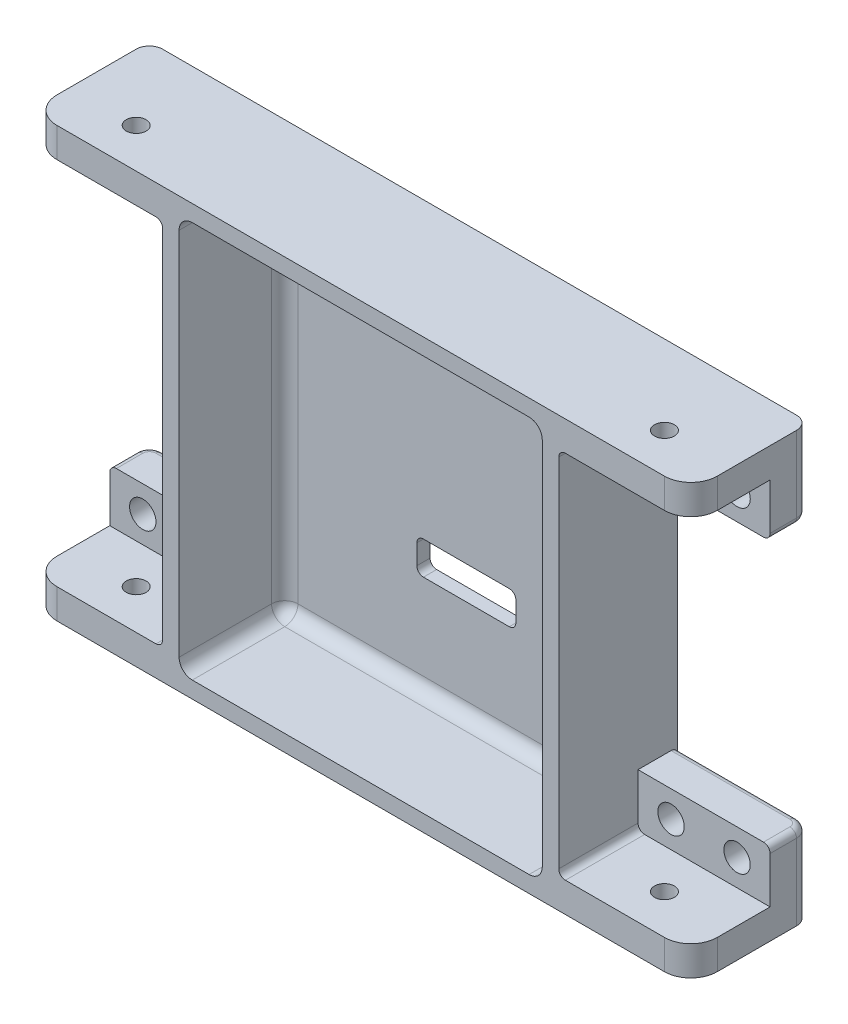
SolidWorks part; units mm, degrees
ref_plane "前视基准面" through (0, 0, 0) normal (0, 0, 1) x (1, 0, 0)
ref_plane "上视基准面" through (0, 0, 0) normal (0, 1, 0) x (1, 0, 0)
ref_plane "右视基准面" through (0, 0, 0) normal (1, 0, 0) x (0, 0, -1)
sketch "草图1" plane through (0, 0, 0) normal (0, 0, 1) x (1, 0, 0)
  line L1 (-50, -32.5) -> (50, -32.5)
  line L2 (-50, -32.5) -> (-50, 32.5)
  line L3 (-50, 32.5) -> (50, 32.5)
  line L4 (50, -32.5) -> (50, 32.5)
  line L5 (-50, -32.5) -> (50, 32.5) construction
  line L6 (-50, 32.5) -> (50, -32.5) construction
  point P0 (0, 0)
  dimension "D1" = 65
  dimension "D2" = 100
extrude "凸台-拉伸1" add sketch "草图1" along normal blind 18
sketch "草图2" plane through (0, 0, 18) normal (0, 0, 1) x (1, 0, 0)
  line L1 (-27.5, -30) -> (27.5, -30)
  line L2 (-27.5, -30) -> (-27.5, 30)
  line L3 (-27.5, 30) -> (27.5, 30)
  line L4 (27.5, -30) -> (27.5, 30)
  line L5 (-27.5, -30) -> (27.5, 30) construction
  line L6 (-27.5, 30) -> (27.5, -30) construction
  point P0 (0, 0)
  dimension "D1" = 55
  dimension "D2" = 60
extrude "切除-拉伸1" cut sketch "草图2" against normal blind 16
sketch "草图3" plane through (0, 0, 2) normal (0, 0, 1) x (1, 0, 0)
  line L0 (-27.5, -30) -> (27.5, -30) construction
  line L1 (-7.5, -15) -> (7.5, -15)
  line L2 (-7.5, -15) -> (-7.5, -10)
  line L3 (-7.5, -10) -> (7.5, -10)
  line L4 (7.5, -15) -> (7.5, -10)
  line L5 (-7.5, -15) -> (7.5, -10) construction
  line L6 (-7.5, -10) -> (7.5, -15) construction
  point P0 (0, -12.5)
  point P7 (-0.7312, -12.5)
  dimension "D1" = 15
  dimension "D2" = 5
  dimension "D3" = 15
extrude "切除-拉伸2" cut sketch "草图3" against normal through all
sketch "草图4" plane through (0, 0, 18) normal (0, 0, 1) x (1, 0, 0)
  line L0 (0, 0) -> (50, 0) construction
  line L1 (50, -32.5) -> (50, 32.5) construction
  line L3 (30, -28) -> (50, -28)
  line L4 (30, -28) -> (30, 28)
  line L5 (30, 28) -> (50, 28)
  line L6 (50, -28) -> (50, 28)
  line L7 (30, -28) -> (50, 28) construction
  line L8 (30, 28) -> (50, -28) construction
  point P5 (40, 0)
  dimension "D1" = 20
  dimension "D2" = 56
extrude "切除-拉伸3" cut sketch "草图4" against normal offset from surface (12 mm away) 6 up to face at (0, -12.5, 0)
sketch "草图5" plane through (0, 0, 6) normal (0, 0, 1) x (1, 0, 0)
  line L0 (0, 0) -> (50, 0) construction
  line L1 (50, -28) -> (50, 28) construction
  line L2 (30, 28) -> (30, -28) construction
  line L3 (30, -20) -> (50, -20)
  line L4 (30, -20) -> (30, 20)
  line L5 (30, 20) -> (50, 20)
  line L6 (50, -20) -> (50, 20)
  line L7 (30, -20) -> (50, 20) construction
  line L8 (30, 20) -> (50, -20) construction
  point P5 (40, 0)
  dimension "D1" = 40
extrude "切除-拉伸4" cut sketch "草图5" against normal through all
sketch "草图6" plane through (0, 0, 6) normal (0, 0, 1) x (1, 0, 0)
  line L0 (50, 20) -> (30, 20) construction
  line L1 (50, 20) -> (50, 28) construction
  line L2 (0, 0) -> (63.6012, 0) construction
  circle A0 centre (45, 24) radius 2
  circle A1 centre (35, 24) radius 2
  circle A2 centre (35, -24) radius 2
  circle A3 centre (45, -24) radius 2
  point P4 (0, 0)
  dimension "D1" = 4
  dimension "D2" = 5
  dimension "D3" = 10
  dimension "D4" = 4
extrude "切除-拉伸5" cut sketch "草图6" against normal through all
sketch "草图7" plane through (0, 32.5, 0) normal (0, 1, 0) x (1, 0, 0)
  line L0 (50, -18) -> (50, 0) construction
  line L1 (50, -18) -> (-50, -18) construction
  circle A0 centre (40, -12) radius 1.5
  dimension "D1" = 10
  dimension "D2" = 6
  dimension "D3" = 3
extrude "切除-拉伸6" cut sketch "草图7" against normal through all
mirror "镜向1" about plane through (0, 0, 0) normal (1, 0, 0) of "切除-拉伸6", "切除-拉伸5", "切除-拉伸4", "切除-拉伸3"
fillet "圆角1" radius 2 8 edges at (27.5, 0, 2) (0, 30, 2) (-27.5, 0, 2) (0, -30, 2) (27.5, 30, 10) (-27.5, 30, 10) (27.5, -30, 10) (-27.5, -30, 10)
fillet "圆角2" radius 1 4 edges at (7.5, -15, 1) (-7.5, -10, 1) (7.5, -10, 1) (-7.5, -15, 1)
fillet "圆角3" radius 4 4 edges at (-50, 30.25, 18) (-50, -30.25, 18) (50, -30.25, 18) (50, 30.25, 18)
fillet "圆角4" radius 2 4 edges at (-50, 26.25, 0) (-50, -26.25, 0) (50, -26.25, 0) (50, 26.25, 0)
fillet "圆角5" radius 1 16 edges at (39, 20, 0) (49.4142, 20, 0.5858) (39, -20, 0) (49.4142, -20, 0.5858) (-39, -20, 0) (-49.4142, -20, 0.5858) (-39, 20, 0) (-49.4142, 20, 0.5858) (50, 20, 4) (50, -20, 4) (-50, -20, 4) (-50, 20, 4) (-30, 28, 12) (-30, -28, 12) (30, -28, 12) (30, 28, 12)
